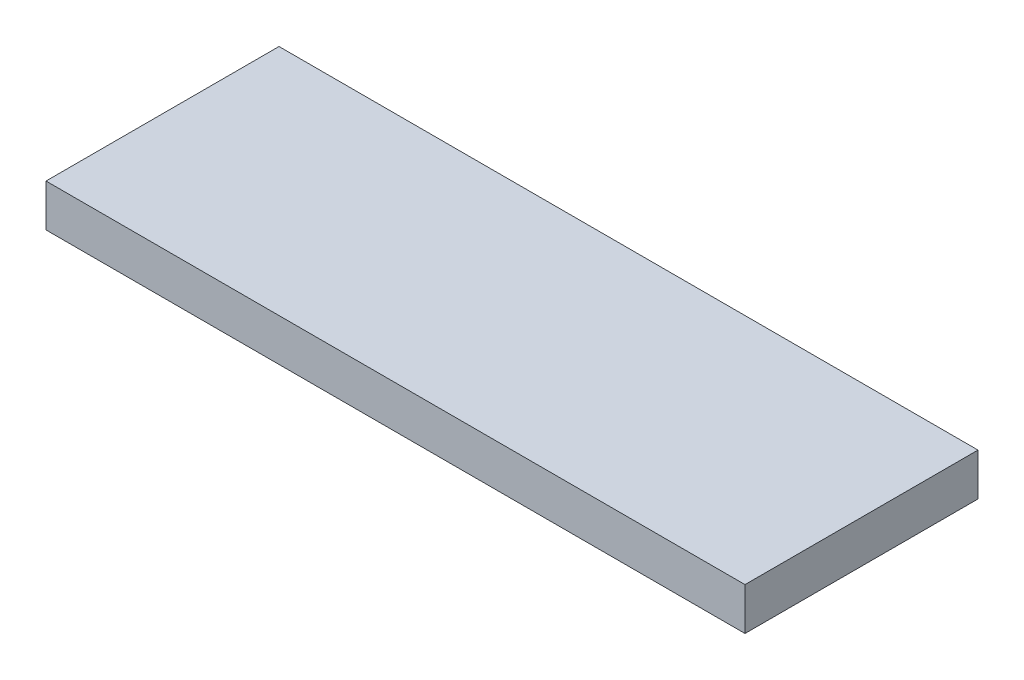
SolidWorks part; units mm, degrees
material "ABS PC"
ref_plane "Front" through (0, 0, 0) normal (0, 0, 1) x (1, 0, 0)
ref_plane "Top" through (0, 0, 0) normal (0, 1, 0) x (1, 0, 0)
ref_plane "Right" through (0, 0, 0) normal (1, 0, 0) x (0, 0, -1)
sketch "Sketch1" plane through (0, 0, 0) normal (0, 1, 0) x (1, 0, 0)
  line L1 (0, 0) -> (165, 0)
  line L2 (0, 0) -> (0, 55)
  line L3 (0, 55) -> (165, 55)
  line L4 (165, 0) -> (165, 55)
  dimension "D1" = 165
  dimension "D2" = 55
extrude "Boss-Extrude1" add sketch "Sketch1" along normal blind 10
